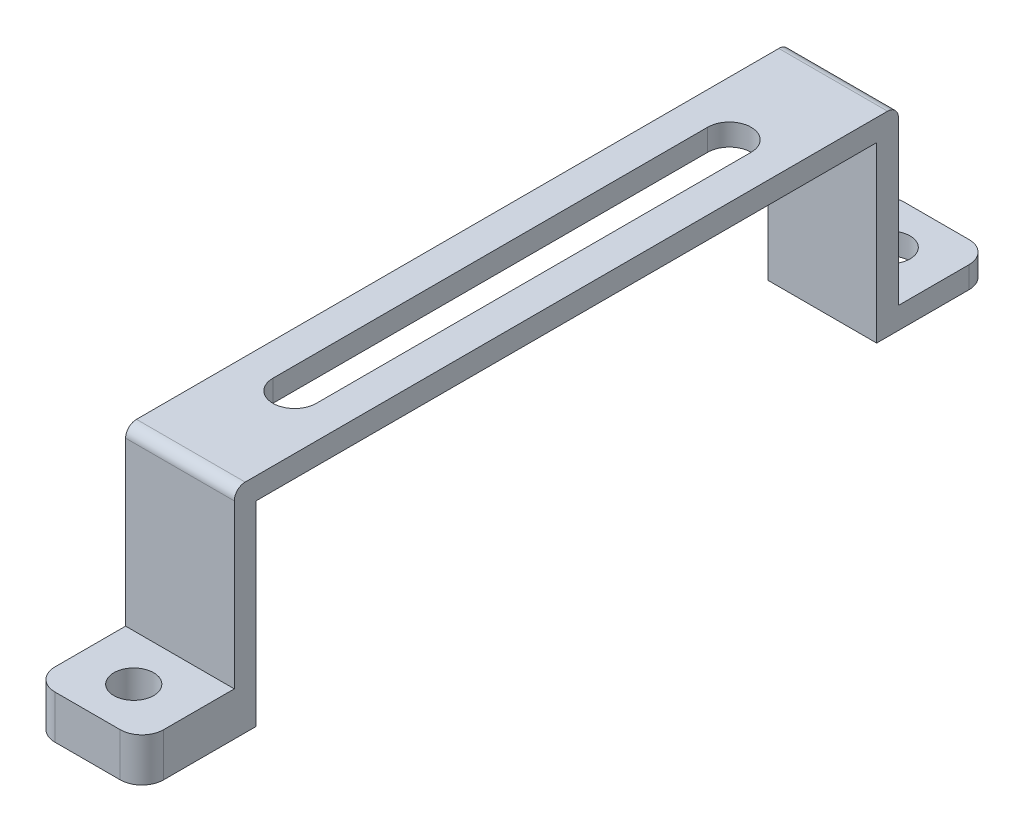
SolidWorks part; units mm, degrees
ref_plane "Front Plane" through (0, 0, 0) normal (0, 0, 1) x (1, 0, 0)
ref_plane "Top Plane" through (0, 0, 0) normal (0, 1, 0) x (1, 0, 0)
ref_plane "Right Plane" through (0, 0, 0) normal (1, 0, 0) x (0, 0, -1)
sketch "Sketch4" plane through (0, 0, 0) normal (0, 1, 0) x (1, 0, 0)
  line L0 (11.7063, 0.0022) -> (11.7063, -56.9978) construction
  line L1 (30.2063, 0.0022) -> (-6.7937, 0.0022) construction
  line L2 (-11.7937, -56.9978) -> (30.2063, -56.9978) construction
  line L3 (-16.7937, -28.4978) -> (40.2063, -28.4978) construction
  line L4 (-16.7937, -9.9978) -> (-16.7937, -51.9978) construction
  line L5 (40.2063, -46.9978) -> (40.2063, -9.9978) construction
  line L6 (11.7063, -8.4978) -> (11.7063, -48.4978) construction
  line L7 (6.7063, 0.0022) -> (16.7063, 0.0022)
  line L8 (6.7063, 0.0022) -> (6.7063, -56.9978)
  line L9 (6.7063, -56.9978) -> (16.7063, -56.9978)
  line L10 (16.7063, 0.0022) -> (16.7063, -56.9978)
  line L11 (13.7063, -8.4978) -> (13.7063, -48.4978)
  line L12 (9.7063, -8.4978) -> (9.7063, -48.4978)
  arc A0 (13.7063, -8.4978) -> (9.7063, -8.4978) centre (11.7063, -8.4978) ccw
  arc A1 (9.7063, -48.4978) -> (13.7063, -48.4978) centre (11.7063, -48.4978) ccw
  point P12 (11.7063, -28.4978)
  point P13 (11.7063, -28.4978)
  point P18 (16.7063, -28.4978)
  point P19 (11.7063, 0.0022)
  point P22 (11.7063, -28.4978)
  dimension "D1" = 10
  dimension "D2" = 2
  dimension "D3" = 40
extrude "Boss-Extrude3" add sketch "Sketch4" along normal blind 2
sketch "Sketch5" plane through (0, 0, 56.9978) normal (0, 0, 1) x (1, 0, 0)
  line L1 (6.7063, 2) -> (16.7063, 2)
  line L2 (6.7063, 2) -> (6.7063, 0)
  line L3 (6.7063, 0) -> (16.7063, 0)
  line L4 (16.7063, 2) -> (16.7063, 0)
extrude "Boss-Extrude4" add sketch "Sketch5" along normal blind 2.05
sketch "Sketch6" plane through (0, 0, 0) normal (0, -1, 0) x (1, 0, 0)
  line L0 (16.7063, 59.0478) -> (16.7063, -0.0022) construction
  line L1 (6.7063, 59.0478) -> (16.7063, 59.0478)
  line L2 (6.7063, 59.0478) -> (6.7063, 57.0478)
  line L3 (6.7063, 57.0478) -> (16.7063, 57.0478)
  line L4 (16.7063, 59.0478) -> (16.7063, 57.0478)
  dimension "D1" = 2
extrude "Boss-Extrude5" add sketch "Sketch6" along normal blind 15.9766
sketch "Sketch7" plane through (0, 0, 59.0478) normal (0, 0, 1) x (1, 0, 0)
  line L0 (6.7063, 2) -> (6.7063, -15.9766) construction
  line L1 (16.7063, -17.9766) -> (6.7063, -17.9766)
  line L2 (16.7063, -17.9766) -> (16.7063, -13.9766)
  line L3 (16.7063, -13.9766) -> (6.7063, -13.9766)
  line L4 (6.7063, -17.9766) -> (6.7063, -13.9766)
  line L5 (16.7063, -15.9766) -> (6.7063, -15.9766) construction
  dimension "D1" = 4
  dimension "D2" = 2
extrude "Boss-Extrude6" add sketch "Sketch7" along normal blind 8.5
sketch "Sketch8" plane through (0, 0, -0.0022) normal (0, 0, -1) x (-1, 0, 0)
  line L1 (-16.7063, 2) -> (-6.7063, 2)
  line L2 (-16.7063, 2) -> (-16.7063, 0)
  line L3 (-16.7063, 0) -> (-6.7063, 0)
  line L4 (-6.7063, 2) -> (-6.7063, 0)
extrude "Boss-Extrude7" add sketch "Sketch8" along normal blind 2.05
sketch "Sketch9" plane through (0, 0, 0) normal (0, -1, 0) x (1, 0, 0)
  line L0 (16.7063, 57.0478) -> (16.7063, -2.0522) construction
  line L1 (6.7063, -2.0522) -> (16.7063, -2.0522)
  line L2 (6.7063, -2.0522) -> (6.7063, -0.0522)
  line L3 (6.7063, -0.0522) -> (16.7063, -0.0522)
  line L4 (16.7063, -2.0522) -> (16.7063, -0.0522)
  dimension "D1" = 2
extrude "Boss-Extrude8" add sketch "Sketch9" along normal blind 15.9766
sketch "Sketch10" plane through (0, 0, -2.0522) normal (0, 0, -1) x (-1, 0, 0)
  line L0 (-6.7063, -15.9766) -> (-6.7063, 2) construction
  line L1 (-16.7063, -15.9766) -> (-6.7063, -15.9766)
  line L2 (-16.7063, -15.9766) -> (-16.7063, -13.9766)
  line L3 (-16.7063, -13.9766) -> (-6.7063, -13.9766)
  line L4 (-6.7063, -15.9766) -> (-6.7063, -13.9766)
  dimension "D1" = 2
extrude "Boss-Extrude9" add sketch "Sketch10" along normal blind 8.5
sketch "Sketch13" plane through (0, -13.9766, 0) normal (0, 1, 0) x (1, 0, 0)
  line L0 (6.7063, 10.5522) -> (16.7063, 10.5522) construction
  line L1 (6.7063, 10.5522) -> (6.7063, 2.0522) construction
  line L2 (6.7063, -67.5478) -> (6.7063, -59.0478) construction
  point P0 (11.7063, 6.3022)
  point P1 (11.7063, -63.2978)
  point P3 (6.7063, -63.2978)
  point P4 (11.7063, 10.5522)
  point P5 (6.7063, 6.3022)
hole_wizard "#6 Clearance Hole1" positions "Sketch14" profile "Sketch15" hole size "#6" standard "ANSI Inch"
sketch "Sketch14" plane through (0, -13.9766, 0) normal (0, 1, 0) x (1, 0, 0)
  point P0 (11.7063, -63.2978)
  point P3 (11.7063, 6.3022)
sketch "Sketch15" plane through (11.7063, -13.9766, 63.2978) normal (1, 0, 0) x (0, 0, 1)
  line L0 (0, 0) -> (0, 8.7189)
  line L1 (0, 8.7189) -> (1.8288, 7.62)
  line L2 (1.8288, 7.62) -> (1.8288, 0)
  line L5 (1.8288, 0) -> (0, 0)
  line L10 (0, 8.7189) -> (-1.8288, 7.62) construction
  line L11 (0, -6.35) -> (0, 107.95) construction
  dimension "Hole Dia." = 3.6576
  dimension "Hole Depth" = 7.62
  dimension "Drill Angle" = 118
fillet "Fillet2" radius 1 2 edges at (11.7063, 2, 59.0478) (11.7063, 2, -2.0522)
fillet "Fillet3" radius 2 4 edges at (16.7063, -15.9766, 67.5478) (6.7063, -15.9766, 67.5478) (16.7063, -14.9766, -10.5522) (6.7063, -14.9766, -10.5522)
sketch "Sketch16" plane through (0, 0, 59.0478) normal (0, 0, -1) x (-1, 0, 0)
  line L1 (-6.7063, -17.9766) -> (-16.7063, -17.9766)
  line L2 (-6.7063, -17.9766) -> (-6.7063, -15.9766)
  line L3 (-6.7063, -15.9766) -> (-16.7063, -15.9766)
  line L4 (-16.7063, -17.9766) -> (-16.7063, -15.9766)
extrude "Boss-Extrude10" add sketch "Sketch16" along normal up to surface (2 mm away) up to face at (11.7063, -7.9883, 57.0478)
